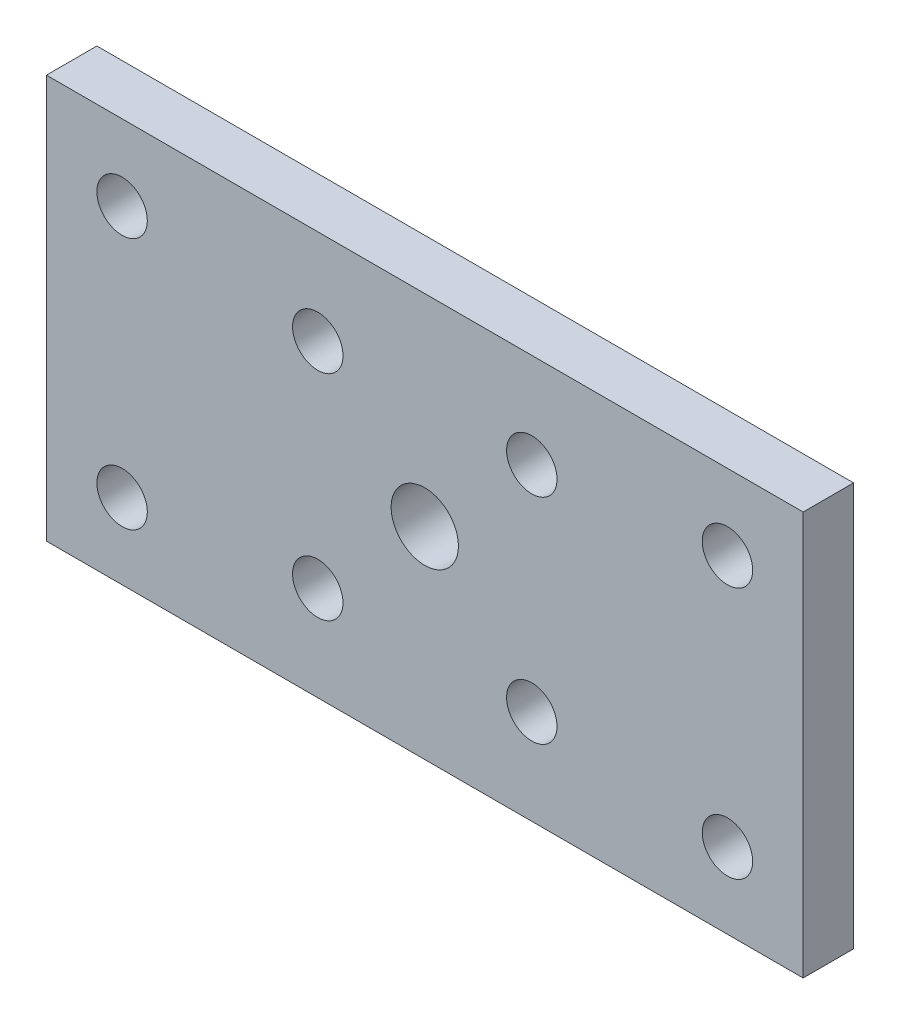
SolidWorks part; units mm, degrees
ref_plane "Alzado" through (0, 0, 0) normal (0, 0, 1) x (1, 0, 0)
ref_plane "Planta" through (0, 0, 0) normal (0, 1, 0) x (1, 0, 0)
ref_plane "Vista lateral" through (0, 0, 0) normal (1, 0, 0) x (0, 0, -1)
sketch "Model" plane through (0, 0, 0) normal (0, 0, 1) x (1, 0, 0)
  line L0 (92.9856, 229.5371) -> (137.9856, 229.5371)
  line L1 (92.9856, 205.5371) -> (137.9856, 205.5371)
  line L2 (92.9856, 229.5371) -> (92.9856, 205.5371)
  line L3 (137.9856, 205.5371) -> (137.9856, 229.5371)
  circle A0 centre (109.1216, 223.901) radius 1.5
  circle A1 centre (121.8496, 211.1731) radius 1.5
  circle A2 centre (121.8496, 223.901) radius 1.5
  circle A3 centre (109.1216, 211.1731) radius 1.5
  circle A4 centre (115.4856, 217.5371) radius 2
  circle A5 centre (97.4856, 225.0371) radius 1.5
  circle A6 centre (97.4856, 210.0371) radius 1.5
  circle A7 centre (133.4856, 225.0371) radius 1.5
  circle A8 centre (133.4856, 210.0371) radius 1.5
extrude "Saliente-Extruir1" add sketch "Model" along normal blind 3
